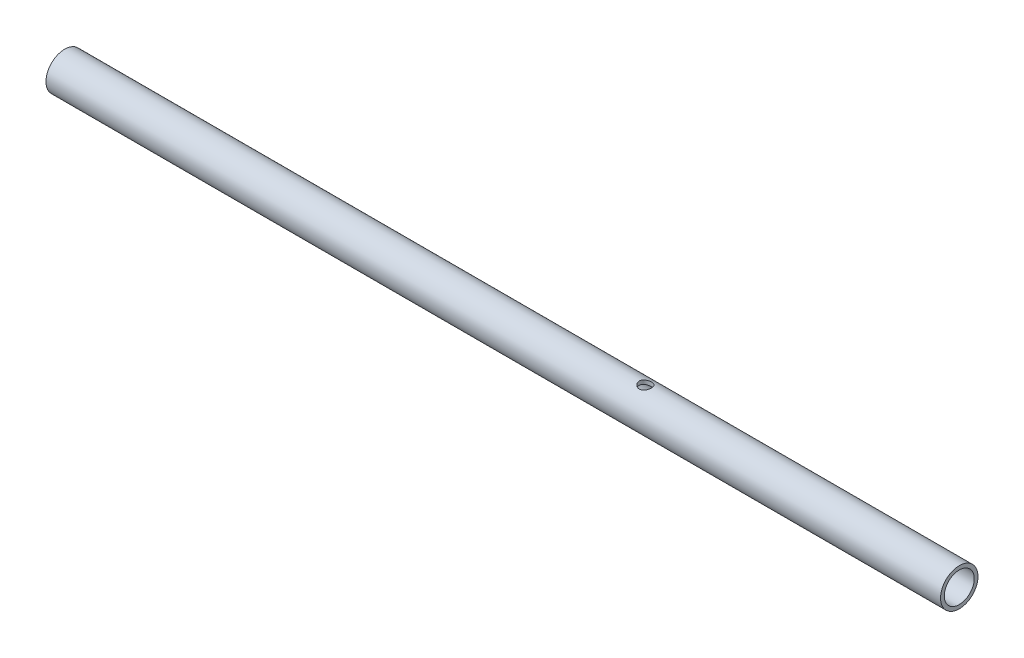
SolidWorks part; units mm, degrees
ref_plane "Front Plane" through (0, 0, 0) normal (0, 0, 1) x (1, 0, 0)
ref_plane "Top Plane" through (0, 0, 0) normal (0, 1, 0) x (1, 0, 0)
ref_plane "Right Plane" through (0, 0, 0) normal (1, 0, 0) x (0, 0, -1)
sketch "Sketch1" plane through (0, 0, 0) normal (1, 0, 0) x (0, 0, -1)
  circle A0 centre (0, 0) radius 20
  circle A1 centre (0, 0) radius 16
  dimension "D1" = 40
  dimension "D2" = 32
extrude "Boss-Extrude1" add sketch "Sketch1" against normal blind 600 and the other way blind 355
ref_plane "Plane1" through (0, 50, 0) normal (0, 1, 0) x (1, 0, 0)
sketch "Sketch2" plane through (0, 0, 0) normal (0, 1, 0) x (1, 0, 0)
  line L0 (41.3741, 0) -> (-150.5723, 0) construction
  line L1 (355, -16) -> (355, 16) construction
  circle A0 centre (20, 0) radius 6.5
  dimension "D2" = 13
  dimension "D1" = 335
extrude "Cut-Extrude1" cut sketch "Sketch2" against normal mid plane 57 contours A0
